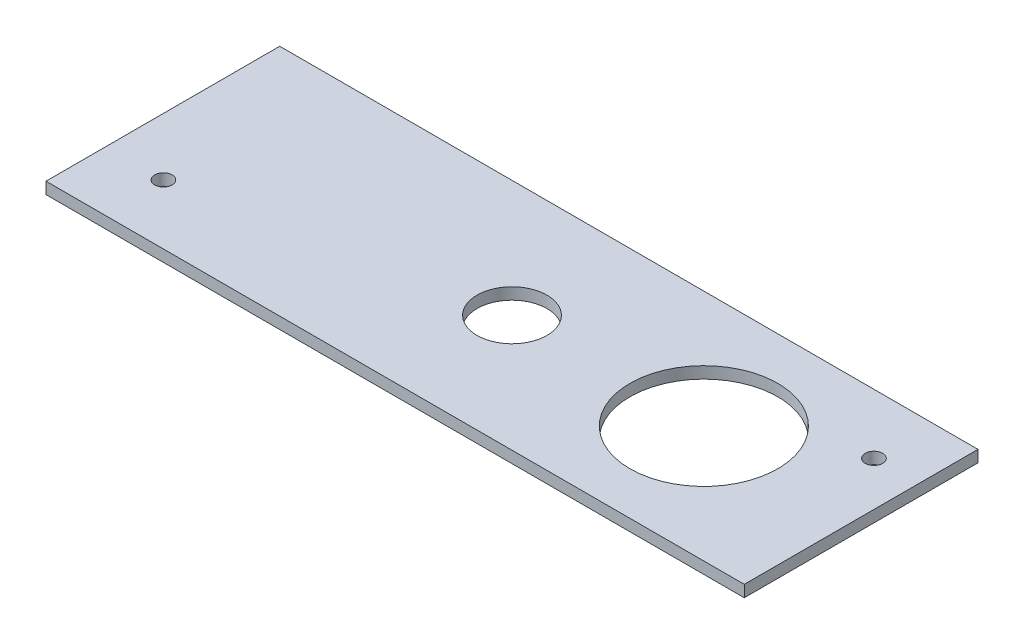
SolidWorks part; units mm, degrees
ref_plane "Front Plane" through (0, 0, 0) normal (0, 0, 1) x (1, 0, 0)
ref_plane "Top Plane" through (0, 0, 0) normal (0, 1, 0) x (1, 0, 0)
ref_plane "Right Plane" through (0, 0, 0) normal (1, 0, 0) x (0, 0, -1)
sketch "Sketch1" plane through (0, 0, 0) normal (0, 1, 0) x (1, 0, 0)
  line L0 (29.972, 0) -> (16.472, 0)
  line L1 (29.972, -10.033) -> (-29.972, -10.033)
  line L2 (29.972, -10.033) -> (29.972, 10.033)
  line L3 (29.972, 10.033) -> (-29.972, 10.033)
  line L4 (-29.972, -10.033) -> (-29.972, 10.033)
  line L5 (29.972, -10.033) -> (-29.972, 10.033) construction
  line L6 (29.972, 10.033) -> (-29.972, -10.033) construction
  line L7 (29.972, 4.9) -> (26.172, 4.9)
  line L8 (29.972, -4.9) -> (-25.028, -4.9)
  circle A0 centre (16.472, 0) radius 6.35
  circle A1 centre (26.172, 4.9) radius 0.75
  circle A2 centre (-25.028, -4.9) radius 0.75
  circle A3 centre (0, 0) radius 3
  point P0 (0, 0)
  dimension "D4" = 12.7
  dimension "D6" = 1.5
  dimension "D10" = 6
  dimension "D1" = 59.944
  dimension "D2" = 20.066
  dimension "D3" = 13.5
  dimension "D5" = 4.9
  dimension "D7" = 3.8
  dimension "D8" = 4.9
  dimension "D9" = 55
extrude "Boss-Extrude1" add sketch "Sketch1" along normal blind 1
